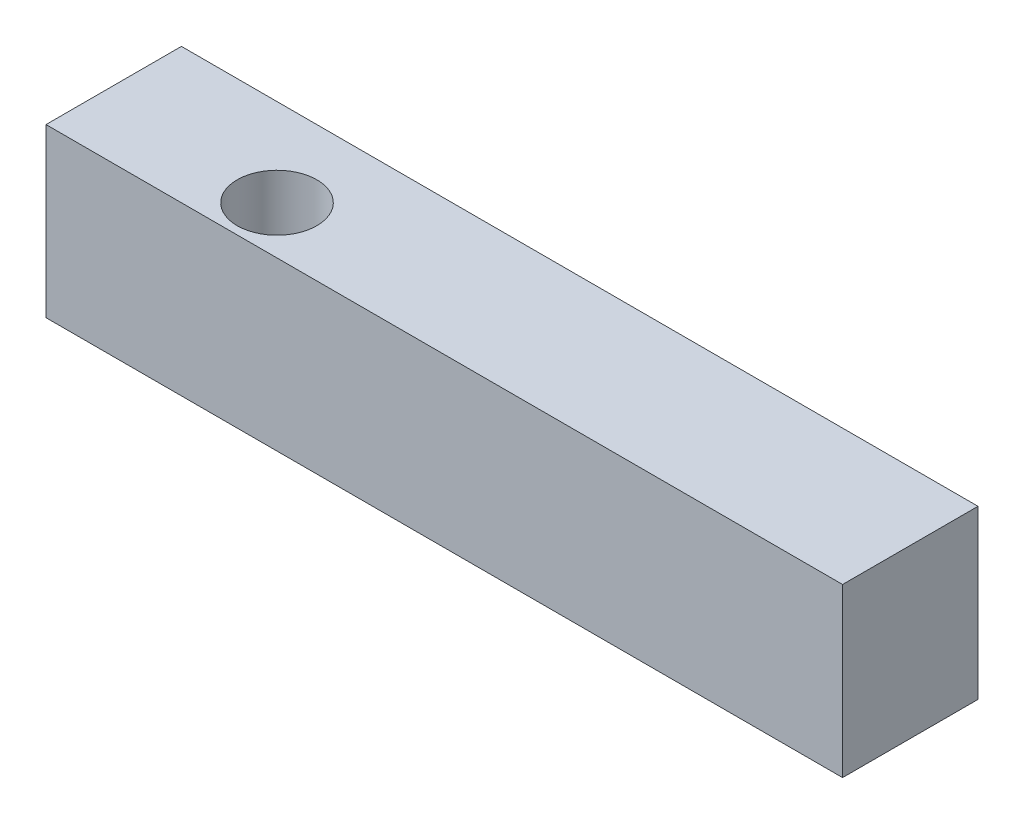
SolidWorks part; units mm, degrees
ref_plane "Front Plane" through (0, 0, 0) normal (0, 0, 1) x (1, 0, 0)
ref_plane "Top Plane" through (0, 0, 0) normal (0, 1, 0) x (1, 0, 0)
ref_plane "Right Plane" through (0, 0, 0) normal (1, 0, 0) x (0, 0, -1)
sketch "Sketch1" plane through (0, 0, 0) normal (0, 0, 1) x (1, 0, 0)
  line L1 (-4.7947, 2.3825) -> (20.6053, 2.3825)
  line L2 (-4.7947, 2.3825) -> (-4.7947, -2.9515)
  line L3 (-4.7947, -2.9515) -> (20.6053, -2.9515)
  line L4 (20.6053, 2.3825) -> (20.6053, -2.9515)
  dimension "D1" = 5.334
  dimension "D2" = 25.4
extrude "Boss-Extrude1" add sketch "Sketch1" along normal blind 4.318
sketch "Sketch2" plane through (0, 2.3825, 0) normal (0, 1, 0) x (1, 0, 0)
  line L1 (-4.7947, -4.318) -> (-4.7947, 0) construction
  line L2 (20.6053, 0) -> (-4.7947, 0) construction
  circle A0 centre (1.0473, -2.794) radius 1.27
  dimension "D1" = 2.794
  dimension "D2" = 5.842
extrude "Cut-Extrude2" cut sketch "Sketch2" against normal through all
equation "\"MDF\"= .21in"
equation "\"Foamcore\"= .13in"
equation "\"Gmaterial\"= \"MDF\""
equation "\"D1@Sketch1\"=\"MDF\""
